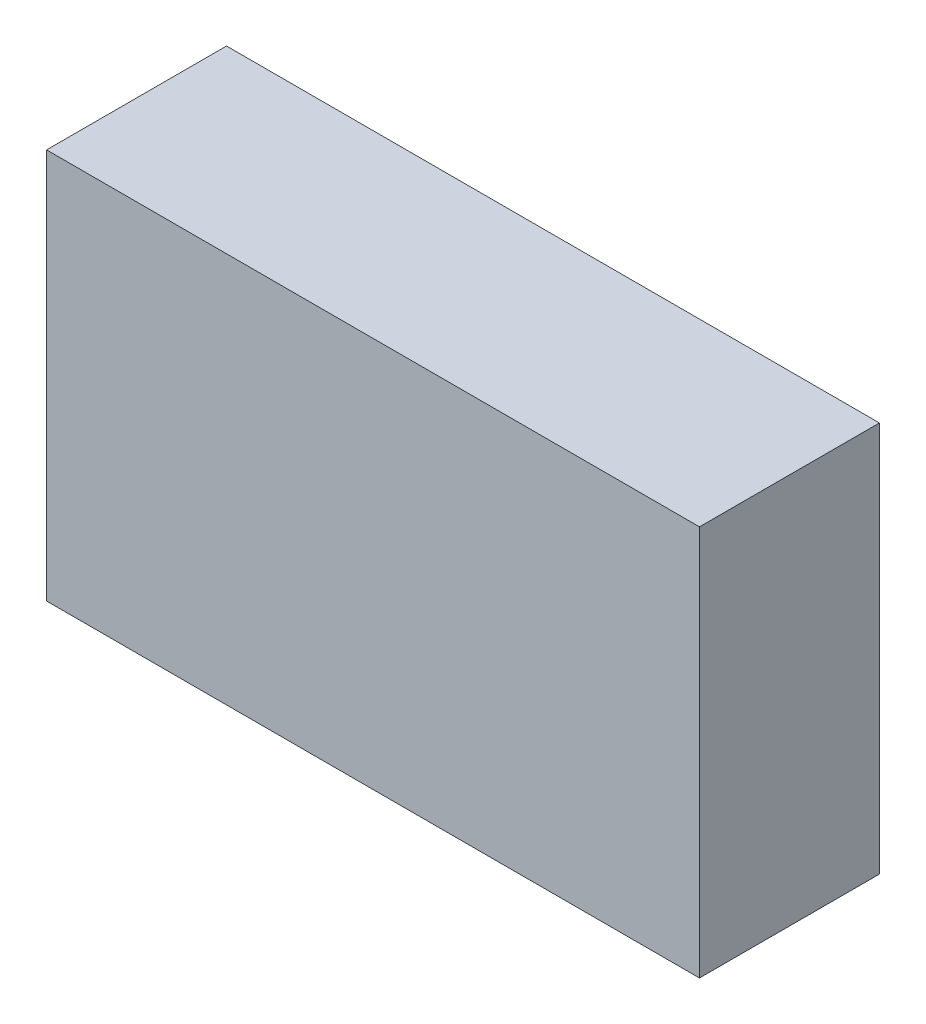
SolidWorks part; units mm, degrees
ref_plane "Front Plane" through (0, 0, 0) normal (0, 0, 1) x (1, 0, 0)
ref_plane "Top Plane" through (0, 0, 0) normal (0, 1, 0) x (1, 0, 0)
ref_plane "Right Plane" through (0, 0, 0) normal (1, 0, 0) x (0, 0, -1)
sketch "Sketch1" plane through (0, 0, 0) normal (0, 0, 1) x (1, 0, 0)
  line L1 (-63.5, 38) -> (63.5, 38)
  line L2 (-63.5, 38) -> (-63.5, -38)
  line L3 (-63.5, -38) -> (63.5, -38)
  line L4 (63.5, 38) -> (63.5, -38)
  line L5 (0, -38) -> (0, 38) construction
  line L6 (-63.5, 0) -> (63.5, 0) construction
  point P0 (0, 0)
  dimension "D1" = 127
  dimension "D2" = 76
extrude "Boss-Extrude1" add sketch "Sketch1" along normal blind 35
